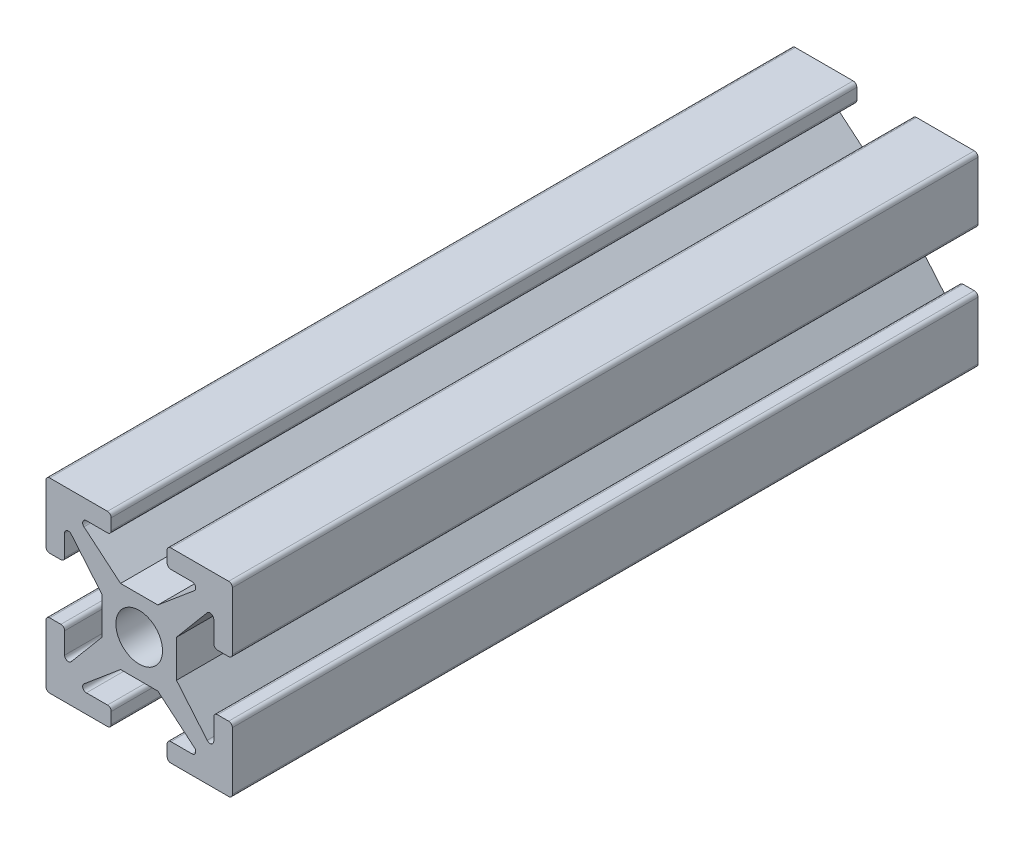
SolidWorks part; units mm, degrees
material "Alliage 1060"
ref_plane "Front Plane" through (0, 0, 0) normal (0, 0, 1) x (1, 0, 0)
ref_plane "Top Plane" through (0, 0, 0) normal (0, 1, 0) x (1, 0, 0)
ref_plane "Right Plane" through (0, 0, 0) normal (1, 0, 0) x (0, 0, -1)
sketch "Sketch1" plane through (0, 0, 0) normal (0, 0, 1) x (1, 0, 0)
  line L0 (0, 2) -> (0, -2) construction
  line L1 (2.4868, 1) -> (2, 1) construction
  line L2 (2.4868, 1) -> (2.4868, -1) construction
  line L3 (-4.8, 5) -> (-1.7, 5)
  line L4 (2, 2) -> (0, 0) construction
  line L5 (5, 5) -> (0, 0) construction
  line L6 (-5, 5) -> (0, 0) construction
  line L7 (5, 1.7) -> (5, 4.8)
  line L8 (-2, -1) -> (-2, 1)
  line L9 (-1, 2) -> (1, 2)
  line L10 (1, 2) -> (2.9626, 3.6468)
  line L11 (2, 1) -> (3.6468, 2.9626)
  line L12 (-2, 2) -> (0, 0) construction
  line L13 (2.834, 4) -> (1.7, 4)
  line L14 (-5, 0) -> (5, 0) construction
  line L15 (-4, 1.7) -> (-4, 2.834)
  line L16 (-5, 5) -> (-1.5, 5)
  line L17 (-5, 5) -> (-5, 1.5)
  line L18 (-4.8, 1.5) -> (-4.2, 1.5)
  line L19 (-1.5, 4.8) -> (-1.5, 4.2)
  line L20 (-2.834, 4) -> (-1.7, 4)
  line L21 (-2.4868, 1) -> (-2.4868, -1) construction
  line L22 (1.5, 4.8) -> (1.5, 4.2)
  line L23 (-2, 1) -> (-3.6468, 2.9626)
  line L24 (-2.4868, 1) -> (-2, 1) construction
  line L25 (-1, 2) -> (-2.9626, 3.6468)
  line L26 (4.8, 1.5) -> (4.2, 1.5)
  line L27 (-5, 1.7) -> (-5, 4.8)
  line L28 (5, 5) -> (5, 1.5)
  line L29 (5, 5) -> (1.5, 5)
  line L30 (4, 1.7) -> (4, 2.834)
  line L31 (2, -1) -> (2, 1)
  line L32 (4.8, 5) -> (1.7, 5)
  line L33 (-2.4868, -1) -> (-2, -1) construction
  line L34 (-2, -2) -> (0, 0) construction
  line L35 (-5, -5) -> (0, 0) construction
  line L36 (5, -5) -> (0, 0) construction
  line L37 (2, -2) -> (0, 0) construction
  line L38 (2.4868, -1) -> (2, -1) construction
  line L39 (4.8, -5) -> (1.7, -5)
  line L40 (4, -1.7) -> (4, -2.834)
  line L41 (5, -5) -> (1.5, -5)
  line L42 (5, -5) -> (5, -1.5)
  line L43 (-5, -1.7) -> (-5, -4.8)
  line L44 (4.8, -1.5) -> (4.2, -1.5)
  line L45 (-1, -2) -> (-2.9626, -3.6468)
  line L46 (-2, -1) -> (-3.6468, -2.9626)
  line L47 (1.5, -4.8) -> (1.5, -4.2)
  line L48 (-2.834, -4) -> (-1.7, -4)
  line L49 (-1.5, -4.8) -> (-1.5, -4.2)
  line L50 (-4.8, -1.5) -> (-4.2, -1.5)
  line L51 (-5, -5) -> (-5, -1.5)
  line L52 (-5, -5) -> (-1.5, -5)
  line L53 (-4, -1.7) -> (-4, -2.834)
  line L54 (2.834, -4) -> (1.7, -4)
  line L55 (2, -1) -> (3.6468, -2.9626)
  line L56 (1, -2) -> (2.9626, -3.6468)
  line L57 (-1, -2) -> (1, -2)
  line L58 (5, -1.7) -> (5, -4.8)
  line L59 (-4.8, -5) -> (-1.7, -5)
  circle A0 centre (0, 0) radius 1.25
  arc A1 (-2.9626, 3.6468) -> (-2.834, 4) centre (-2.834, 3.8) cw
  arc A2 (-3.6468, 2.9626) -> (-4, 2.834) centre (-3.8, 2.834) ccw
  arc A3 (-1.7, 4) -> (-1.5, 4.2) centre (-1.7, 4.2) ccw
  arc A4 (-4, 1.7) -> (-4.2, 1.5) centre (-4.2, 1.7) cw
  arc A5 (-1.7, 5) -> (-1.5, 4.8) centre (-1.7, 4.8) cw
  arc A6 (-5, 1.7) -> (-4.8, 1.5) centre (-4.8, 1.7) ccw
  arc A7 (-5, 4.8) -> (-4.8, 5) centre (-4.8, 4.8) cw
  arc A8 (5, 4.8) -> (4.8, 5) centre (4.8, 4.8) ccw
  arc A9 (5, 1.7) -> (4.8, 1.5) centre (4.8, 1.7) cw
  arc A10 (1.7, 5) -> (1.5, 4.8) centre (1.7, 4.8) ccw
  arc A11 (4, 1.7) -> (4.2, 1.5) centre (4.2, 1.7) ccw
  arc A12 (1.7, 4) -> (1.5, 4.2) centre (1.7, 4.2) cw
  arc A13 (3.6468, 2.9626) -> (4, 2.834) centre (3.8, 2.834) cw
  arc A14 (2.9626, 3.6468) -> (2.834, 4) centre (2.834, 3.8) ccw
  arc A15 (2.9626, -3.6468) -> (2.834, -4) centre (2.834, -3.8) cw
  arc A16 (3.6468, -2.9626) -> (4, -2.834) centre (3.8, -2.834) ccw
  arc A17 (1.7, -4) -> (1.5, -4.2) centre (1.7, -4.2) ccw
  arc A18 (4, -1.7) -> (4.2, -1.5) centre (4.2, -1.7) cw
  arc A19 (1.7, -5) -> (1.5, -4.8) centre (1.7, -4.8) cw
  arc A20 (5, -1.7) -> (4.8, -1.5) centre (4.8, -1.7) ccw
  arc A21 (5, -4.8) -> (4.8, -5) centre (4.8, -4.8) cw
  arc A22 (-5, -4.8) -> (-4.8, -5) centre (-4.8, -4.8) ccw
  arc A23 (-5, -1.7) -> (-4.8, -1.5) centre (-4.8, -1.7) cw
  arc A24 (-1.7, -5) -> (-1.5, -4.8) centre (-1.7, -4.8) ccw
  arc A25 (-4, -1.7) -> (-4.2, -1.5) centre (-4.2, -1.7) ccw
  arc A26 (-1.7, -4) -> (-1.5, -4.2) centre (-1.7, -4.2) cw
  arc A27 (-3.6468, -2.9626) -> (-4, -2.834) centre (-3.8, -2.834) cw
  arc A28 (-2.9626, -3.6468) -> (-2.834, -4) centre (-2.834, -3.8) ccw
  point P0 (0, 0)
  point P4 (-3.3835, 4)
  point P6 (0, 0)
  point P7 (2, 0)
  point P10 (3.3835, -4)
  point P14 (-4, 3.3835)
  point P71 (4, 3.3835)
  point P72 (3.3835, 4)
  point P75 (-2.4868, 0)
  point P80 (2.4868, 0)
  point P129 (-2, 0)
  point P130 (4, -3.3835)
  point P131 (-4, -3.3835)
  point P132 (-3.3835, -4)
  dimension "D5" = 2.5
  dimension "D2" = 0.2
  dimension "D6" = 1.5
  dimension "D8" = 1
  dimension "D10" = 50
extrude "Boss-Extrude1" add sketch "Sketch1" along normal blind 40 contours A28 L45 L57 L56 A15 L54 A17 L47 A19 L39 A21 L42 A20 L44 A18 L40 A16 L55 L31 L11 A13 L30 A11 L26 A9 L7 A8 L29 A10 L22 A12 L13 A14 L10 L9 L25 A1 L20 A3 L19 A5 L3 A7 L17 A6 L18 A4 L15 A2 L23 L8
ref_point "Point1" [suppressed]
ref_point "Point2"
ref_plane "SYM" through (0, 0, 20) normal (0, 0, 1) x (1, 0, 0)
move or copy body "Corps-Déplacer/Copier1" [suppressed] bodies to move or copy 101
move or copy body "Corps-Déplacer/Copier2" [suppressed] bodies to move or copy 101
